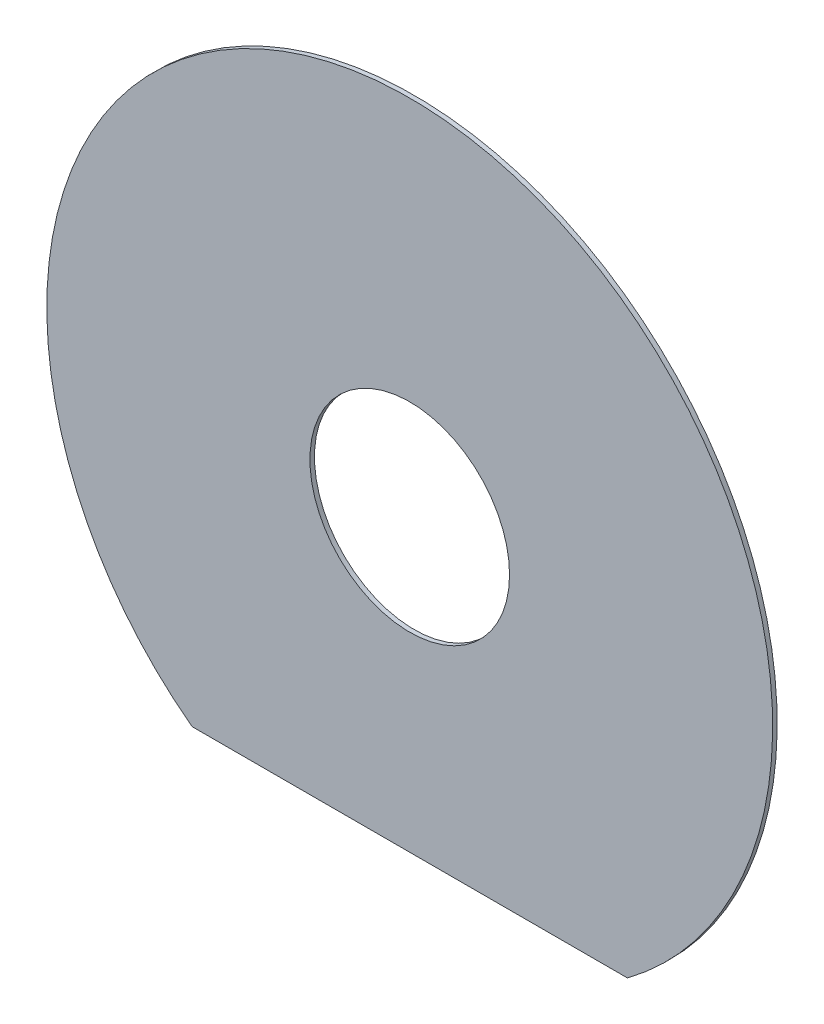
SolidWorks part; units mm, degrees
ref_plane "Front Plane" through (0, 0, 0) normal (0, 0, 1) x (1, 0, 0)
ref_plane "Top Plane" through (0, 0, 0) normal (0, 1, 0) x (1, 0, 0)
ref_plane "Right Plane" through (0, 0, 0) normal (1, 0, 0) x (0, 0, -1)
sketch "Sketch2" plane through (0, 0, 0) normal (0, 0, 1) x (1, 0, 0)
  line L0 (-152.4, -203.2) -> (152.4, -203.2)
  arc A0 (152.4, -203.2) -> (-152.4, -203.2) centre (0, 0) ccw
  circle A1 centre (0, 0) radius 69.85
  dimension "D1" = 304.8
extrude "Boss-Extrude1" add sketch "Sketch2" along normal blind 3.175
